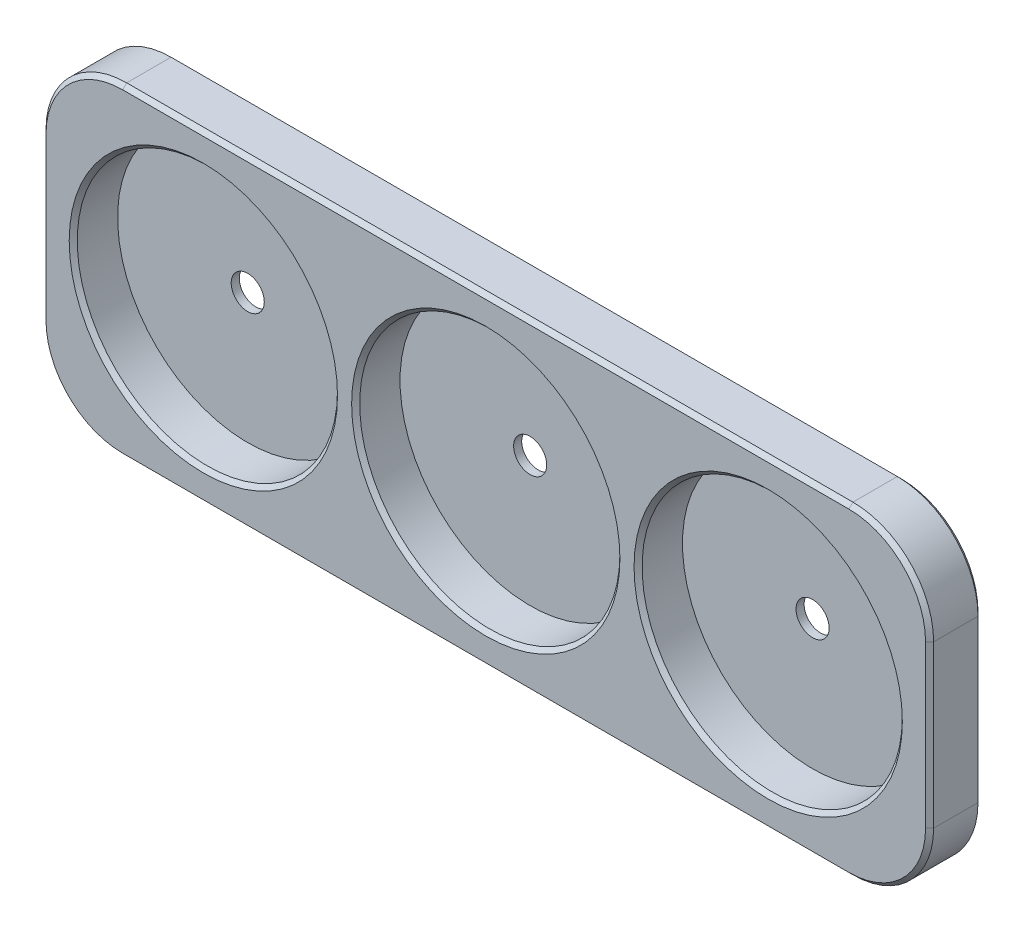
SolidWorks part; units mm, degrees
ref_plane "Front Plane" through (0, 0, 0) normal (0, 0, 1) x (1, 0, 0)
ref_plane "Top Plane" through (0, 0, 0) normal (0, 1, 0) x (1, 0, 0)
ref_plane "Right Plane" through (0, 0, 0) normal (1, 0, 0) x (0, 0, -1)
sketch "Sketch1" plane through (0, 0, 0) normal (0, 0, 1) x (1, 0, 0)
  line L1 (-55, 20) -> (55, 20)
  line L2 (-55, 20) -> (-55, -20)
  line L3 (-55, -20) -> (55, -20)
  line L4 (55, 20) -> (55, -20)
  line L5 (-55, 20) -> (55, -20) construction
  line L6 (-55, -20) -> (55, 20) construction
  point P0 (0, 0)
  dimension "D1" = 40
  dimension "D2" = 110
extrude "Boss-Extrude1" add sketch "Sketch1" along normal blind 6.5
sketch "Sketch2" plane through (0, 0, 6.5) normal (0, 0, 1) x (1, 0, 0)
  circle A0 centre (0, 0) radius 16.125
  circle A1 centre (35, 0) radius 16.125
  circle A2 centre (-35, 0) radius 16.125
  dimension "D1" = 32.25
  dimension "D2" = 70
  dimension "D3" = 35
extrude "Cut-Extrude1" cut sketch "Sketch2" against normal blind 5.5
fillet "Fillet1" radius 10 4 edges at (55, -20, 3.25) (55, 20, 3.25) (-55, 20, 3.25) (-55, -20, 3.25)
sketch "Sketch3" plane through (0, 0, 1) normal (0, 0, 1) x (1, 0, 0)
  circle A0 centre (0, 0) radius 2.05
  circle A1 centre (35, 0) radius 2.05
  circle A2 centre (-35, 0) radius 2.05
  dimension "D1" = 4.1
extrude "Cut-Extrude2" cut sketch "Sketch3" against normal through all
chamfer "Chamfer1" distance 0.5 angle 45 19 edges at (51.125, 0, 6.5) (16.125, 0, 6.5) (-18.875, 0, 6.5) (0, 20, 0) (-52.0711, 17.0711, 0) (52.0711, 17.0711, 0) (-55, 0, 0) (55, 0, 0) (-52.0711, -17.0711, 0) (52.0711, -17.0711, 0) (0, -20, 0) (0, 20, 6.5) (-52.0711, 17.0711, 6.5) (52.0711, 17.0711, 6.5) (-55, 0, 6.5) (55, 0, 6.5) (-52.0711, -17.0711, 6.5) (52.0711, -17.0711, 6.5) (0, -20, 6.5)
